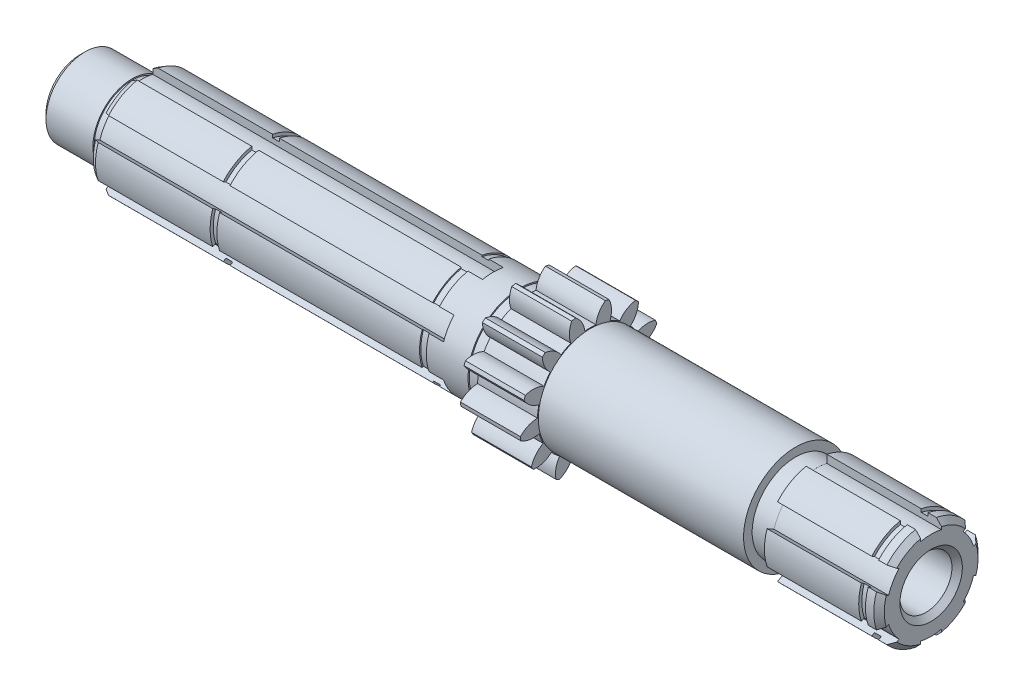
SolidWorks part; units mm, degrees
ref_plane "前视基准面" through (0, 0, 0) normal (0, 0, 1) x (1, 0, 0)
ref_plane "上视基准面" through (0, 0, 0) normal (0, 1, 0) x (1, 0, 0)
ref_plane "右视基准面" through (0, 0, 0) normal (1, 0, 0) x (0, 0, -1)
sketch "草图1" plane through (0, 0, 0) normal (0, 0, 1) x (1, 0, 0)
  line L0 (-46.8808, 0) -> (68.5307, 0) construction
  line L1 (-80.9834, 0) -> (-80.9834, 7.5)
  line L2 (-80.9834, 7.5) -> (-70.9834, 7.5)
  line L3 (-70.9834, 7.5) -> (-70.9834, 7.25)
  line L4 (-70.9834, 7.25) -> (-68.9834, 7.25)
  line L5 (-68.9834, 7.25) -> (-68.9834, 10)
  line L6 (-68.9834, 10) -> (-45.9834, 10)
  line L7 (-45.9834, 10) -> (-45.9834, 9.4)
  line L8 (-45.9834, 9.4) -> (-44.6834, 9.4)
  line L9 (-44.6834, 9.4) -> (-44.6834, 10)
  line L10 (-44.6834, 10) -> (-5.7834, 10)
  line L11 (-5.7834, 10) -> (-5.7834, 9.75)
  line L12 (-5.7834, 9.75) -> (-4.4834, 9.75)
  line L13 (-4.4834, 9.75) -> (-4.4834, 10)
  line L14 (-4.4834, 10) -> (3.5166, 10)
  line L15 (3.5166, 10) -> (3.5166, 9.75)
  line L16 (3.5166, 9.75) -> (5.5166, 9.75)
  line L17 (-80.9834, 0) -> (5.5166, 0)
  line L18 (5.5166, 9.75) -> (5.5166, 0)
  point P20 (0, 0)
  dimension "D1" = 7.5
  dimension "D2" = 10
  dimension "D3" = 10
  dimension "D4" = 0.6
  dimension "D5" = 9.75
  dimension "D6" = 75.2
  dimension "D7" = 35
  dimension "D8" = 36.3
  dimension "D9" = 10
  dimension "D10" = 84.5
  dimension "D11" = 86.5
revolve "旋转1" add sketch "草图1" angle 360 about L0
sketch "草图4" plane through (5.5166, 0, 0) normal (1, 0, 0) x (0, 0, -1)
  arc A0 (2.8664, 13.1922) -> (1.0583, 10.0947) centre (5.5738, 9.5354) ccw
  arc A1 (3.7542, 9.4302) -> (3.5927, 13.0132) centre (-0.504, 11.0334) ccw
  arc A2 (3.5927, 13.0132) -> (2.8664, 13.1922) centre (0, 0) ccw
  arc A3 (8.6687, 10.349) -> (5.6283, 8.4466) centre (9.3666, 5.8529) ccw
  arc A4 (7.7066, 6.6054) -> (9.2287, 9.853) centre (4.6812, 10.0038) ccw
  arc A5 (-1.0583, 10.0947) -> (-2.8664, 13.1922) centre (-5.5738, 9.5354) ccw
  arc A6 (-2.8664, 13.1922) -> (-3.5927, 13.0132) centre (0, 0) ccw
  arc A7 (-3.5927, 13.0132) -> (-3.7542, 9.4302) centre (0.504, 11.0334) ccw
  arc A8 (9.2287, 9.853) -> (8.6687, 10.349) centre (0, 0) ccw
  arc A9 (12.4852, 5.1351) -> (8.9089, 4.8635) centre (11.0137, 0.8296) ccw
  arc A10 (9.8935, 2.2673) -> (12.7505, 4.4356) centre (8.794, 6.6825) ccw
  arc A11 (12.7505, 4.4356) -> (12.4852, 5.1351) centre (0, 0) ccw
  arc A12 (13.4415, -1.2553) -> (10.1486, 0.1662) centre (10.1377, -4.3838) ccw
  arc A13 (9.814, -2.5901) -> (13.3513, -1.9979) centre (10.8922, 1.8303) ccw
  arc A14 (13.3513, -1.9979) -> (13.4415, -1.2553) centre (0, 0) ccw
  arc A15 (11.3185, -7.3581) -> (9.0634, -4.5691) centre (6.9392, -8.5929) ccw
  arc A16 (7.4861, -6.8542) -> (10.8935, -7.9738) centre (10.4951, -3.4412) ccw
  arc A17 (10.8935, -7.9738) -> (11.3185, -7.3581) centre (0, 0) ccw
  arc A18 (6.6025, -11.7752) -> (5.9019, -8.2577) centre (2.1511, -10.8334) ccw
  arc A19 (3.4433, -9.5481) -> (5.9402, -12.1229) centre (7.6938, -7.9244) ccw
  arc A20 (5.9402, -12.1229) -> (6.6025, -11.7752) centre (0, 0) ccw
  arc A21 (0.374, -13.4948) -> (1.3883, -10.0546) centre (-3.1298, -10.5922) ccw
  arc A22 (-1.3883, -10.0546) -> (-0.374, -13.4948) centre (3.1298, -10.5922) ccw
  arc A23 (-0.374, -13.4948) -> (0.374, -13.4948) centre (0, 0) ccw
  arc A24 (-5.9402, -12.1229) -> (-3.4433, -9.5481) centre (-7.6938, -7.9244) ccw
  arc A25 (-5.9019, -8.2577) -> (-6.6025, -11.7752) centre (-2.1511, -10.8334) ccw
  arc A26 (-6.6025, -11.7752) -> (-5.9402, -12.1229) centre (0, 0) ccw
  arc A27 (-10.8935, -7.9738) -> (-7.4861, -6.8542) centre (-10.4951, -3.4412) ccw
  arc A28 (-9.0634, -4.5691) -> (-11.3185, -7.3581) centre (-6.9392, -8.5929) ccw
  arc A29 (-11.3185, -7.3581) -> (-10.8935, -7.9738) centre (0, 0) ccw
  arc A30 (-13.3513, -1.9979) -> (-9.814, -2.5901) centre (-10.8922, 1.8303) ccw
  arc A31 (-10.1486, 0.1662) -> (-13.4415, -1.2553) centre (-10.1377, -4.3838) ccw
  arc A32 (-13.4415, -1.2553) -> (-13.3513, -1.9979) centre (0, 0) ccw
  arc A33 (-12.7505, 4.4356) -> (-9.8935, 2.2673) centre (-8.794, 6.6825) ccw
  arc A34 (-8.9089, 4.8635) -> (-12.4852, 5.1351) centre (-11.0137, 0.8296) ccw
  arc A35 (-12.4852, 5.1351) -> (-12.7505, 4.4356) centre (0, 0) ccw
  arc A36 (-9.2287, 9.853) -> (-7.7066, 6.6054) centre (-4.6812, 10.0038) ccw
  arc A37 (-5.6283, 8.4466) -> (-8.6687, 10.349) centre (-9.3666, 5.8529) ccw
  arc A38 (-8.6687, 10.349) -> (-9.2287, 9.853) centre (0, 0) ccw
  arc A39 (-9.814, -2.5901) -> (-9.0634, -4.5691) centre (0, 0) ccw
  arc A40 (-7.4861, -6.8542) -> (-5.9019, -8.2577) centre (0, 0) ccw
  arc A41 (-3.4433, -9.5481) -> (-1.3883, -10.0546) centre (0, 0) ccw
  arc A42 (1.3883, -10.0546) -> (3.4433, -9.5481) centre (0, 0) ccw
  arc A43 (5.9019, -8.2577) -> (7.4861, -6.8542) centre (0, 0) ccw
  arc A44 (9.0634, -4.5691) -> (9.814, -2.5901) centre (0, 0) ccw
  arc A45 (10.1486, 0.1662) -> (9.8935, 2.2673) centre (0, 0) ccw
  arc A46 (8.9089, 4.8635) -> (7.7066, 6.6054) centre (0, 0) ccw
  arc A47 (5.6283, 8.4466) -> (3.7542, 9.4302) centre (0, 0) ccw
  arc A48 (1.0583, 10.0947) -> (-1.0583, 10.0947) centre (0, 0) ccw
  arc A49 (-3.7542, 9.4302) -> (-5.6283, 8.4466) centre (0, 0) ccw
  arc A50 (-7.7066, 6.6054) -> (-8.9089, 4.8635) centre (0, 0) ccw
  arc A51 (-9.8935, 2.2673) -> (-10.1486, 0.1662) centre (0, 0) ccw
  point P82 (0, 0)
  dimension "D2" = 13.5
  dimension "D3" = 20.3
  dimension "D1" = 13
extrude "凸台-拉伸1" add sketch "草图4" along normal blind 11.5
sketch "草图5" plane through (0, 0, 0) normal (0, 0, 1) x (1, 0, 0)
  line L0 (30.7294, 0) -> (-10.5203, 0) construction
  line L1 (12.0035, 0) -> (17.0166, 9.75)
  line L2 (17.0166, 6.6054) -> (17.0166, 9.853) construction
  line L3 (17.0166, 9.75) -> (14.0166, 9.75)
  line L4 (14.0166, 9.75) -> (14.0166, 10)
  line L5 (14.0166, 10) -> (56.4166, 10)
  line L6 (56.4166, 10) -> (56.4166, 8.35)
  line L7 (56.4166, 8.35) -> (60.4166, 8.35)
  line L8 (60.4166, 8.35) -> (60.4166, 10)
  line L9 (60.4166, 10) -> (78.5166, 10)
  line L10 (78.5166, 10) -> (78.5166, 9.4)
  line L11 (78.5166, 9.4) -> (79.8166, 9.4)
  line L12 (79.8166, 9.4) -> (79.8166, 10)
  line L13 (79.8166, 10) -> (82.4166, 10)
  line L14 (82.4166, 10) -> (82.4166, 0)
  line L15 (82.4166, 0) -> (12.0035, 0)
revolve "旋转2" add sketch "草图5" angle 360 about L15
sketch "草图6" plane through (-68.9834, 0, 0) normal (-1, 0, 0) x (0, 0, 1)
  line L0 (0, 10.7759) -> (0, -4.9329) construction
  line L1 (7.4853, 6.631) -> (6.1545, 5.8627)
  line L2 (-2, 9.798) -> (-2, 8.2614)
  line L3 (2, 9.798) -> (2, 8.2614)
  line L4 (9.4853, 3.1669) -> (8.1545, 2.3986)
  line L5 (9.4853, -3.1669) -> (8.1545, -2.3986)
  line L6 (7.4853, -6.631) -> (6.1545, -5.8627)
  line L7 (2, -9.798) -> (2, -8.2614)
  line L8 (-2, -9.798) -> (-2, -8.2614)
  line L9 (-7.4853, -6.631) -> (-6.1545, -5.8627)
  line L10 (-9.4853, -3.1669) -> (-8.1545, -2.3986)
  line L11 (-9.4853, 3.1669) -> (-8.1545, 2.3986)
  line L12 (-7.4853, 6.631) -> (-6.1545, 5.8627)
  arc A0 (-6.1545, 5.8627) -> (-8.1545, 2.3986) centre (0, 0) ccw
  circle A1 centre (0, 0) radius 10 construction
  arc A2 (2, 9.798) -> (-2, 9.798) centre (0, 0) ccw
  arc A3 (9.4853, 3.1669) -> (7.4853, 6.631) centre (0, 0) ccw
  arc A4 (7.4853, -6.631) -> (9.4853, -3.1669) centre (0, 0) ccw
  arc A5 (-2, -9.798) -> (2, -9.798) centre (0, 0) ccw
  arc A6 (-9.4853, -3.1669) -> (-7.4853, -6.631) centre (0, 0) ccw
  arc A7 (-7.4853, 6.631) -> (-9.4853, 3.1669) centre (0, 0) ccw
  arc A8 (2, 8.2614) -> (-2, 8.2614) centre (0, 0) ccw
  arc A9 (8.1545, 2.3986) -> (6.1545, 5.8627) centre (0, 0) ccw
  arc A10 (6.1545, -5.8627) -> (8.1545, -2.3986) centre (0, 0) ccw
  arc A11 (-2, -8.2614) -> (2, -8.2614) centre (0, 0) ccw
  arc A12 (-8.1545, -2.3986) -> (-6.1545, -5.8627) centre (0, 0) ccw
  point P10 (0, 9.798)
  point P35 (0, 0)
  dimension "D1" = 17
  dimension "D3" = 6
  dimension "D2" = 2
extrude "切除-拉伸3" cut sketch "草图6" against normal blind 67.3
sketch "草图7" plane through (82.4166, 0, 0) normal (1, 0, 0) x (0, 0, -1)
  line L0 (7.4853, 6.631) -> (6.1545, 5.8627)
  line L1 (-2, 9.798) -> (-2, 8.2614)
  line L2 (2, 9.798) -> (2, 8.2614)
  line L3 (9.4853, 3.1669) -> (8.1545, 2.3986)
  line L4 (9.4853, -3.1669) -> (8.1545, -2.3986)
  line L5 (7.4853, -6.631) -> (6.1545, -5.8627)
  line L6 (2, -9.798) -> (2, -8.2614)
  line L7 (-2, -9.798) -> (-2, -8.2614)
  line L8 (-7.4853, -6.631) -> (-6.1545, -5.8627)
  line L9 (-9.4853, -3.1669) -> (-8.1545, -2.3986)
  line L10 (-9.4853, 3.1669) -> (-8.1545, 2.3986)
  line L11 (-7.4853, 6.631) -> (-6.1545, 5.8627)
  arc A0 (-6.1545, 5.8627) -> (-8.1545, 2.3986) centre (0, 0) ccw
  arc A1 (2, 9.798) -> (-2, 9.798) centre (0, 0) ccw
  arc A2 (9.4853, 3.1669) -> (7.4853, 6.631) centre (0, 0) ccw
  arc A3 (7.4853, -6.631) -> (9.4853, -3.1669) centre (0, 0) ccw
  arc A4 (-2, -9.798) -> (2, -9.798) centre (0, 0) ccw
  arc A5 (-9.4853, -3.1669) -> (-7.4853, -6.631) centre (0, 0) ccw
  arc A6 (-7.4853, 6.631) -> (-9.4853, 3.1669) centre (0, 0) ccw
  arc A7 (2, 8.2614) -> (-2, 8.2614) centre (0, 0) ccw
  arc A8 (8.1545, 2.3986) -> (6.1545, 5.8627) centre (0, 0) ccw
  arc A9 (6.1545, -5.8627) -> (8.1545, -2.3986) centre (0, 0) ccw
  arc A10 (-2, -8.2614) -> (2, -8.2614) centre (0, 0) ccw
  arc A11 (-8.1545, -2.3986) -> (-6.1545, -5.8627) centre (0, 0) ccw
  point P3 (0, 9.798)
  point P26 (-5.8073, -0.3567)
  point P27 (0, 0)
  dimension "D1" = 17
  dimension "D2" = 2
extrude "切除-拉伸4" cut sketch "草图7" along direction (-1, 0, 0) on the side against the normal up to next (22 mm away)
sketch "草图8" plane through (-80.9834, 0, 0) normal (-1, 0, 0) x (0, 0, 1)
  circle A0 centre (0, 0) radius 4
  dimension "D1" = 8
extrude "切除-拉伸5" cut sketch "草图8" against normal through all
sketch "草图9" plane through (82.4166, 0, 0) normal (1, 0, 0) x (0, 0, -1)
  circle A0 centre (0, 0) radius 5
extrude "切除-拉伸7" cut sketch "草图9" along direction (-1, 0, 0) on the side against the normal up to surface (78.9 mm away)
chamfer "倒角1" distance 1 angle 45 7 edges at (82.4166, 0, -5)
chamfer "倒角2" distance 1 angle 45 2 edges at (-80.9834, 0, 4) (-80.9834, 0, 7.5)
chamfer "倒角3" distance 1 angle 30 6 edges at (-68.9834, 0, 10) (-68.9834, -8.6603, 5) (-68.9834, -8.6603, -5) (-68.9834, 0, -10) (-68.9834, 8.6603, 5) (-68.9834, 8.6603, -5)
sketch "草图10" plane through (0, 0, 0) normal (0, 1, 0) x (1, 0, 0)
  line L0 (-96.0854, 0) -> (89.4167, 0) construction
  line L1 (82.4166, -2) -> (82.4166, 2) construction
  line L2 (-80.9834, 6.5) -> (-80.9834, -6.5) construction
  circle A0 centre (35.4166, 0) radius 1
  circle A1 centre (-51.9834, 0) radius 1
  dimension "D1" = 47
  dimension "D2" = 29
extrude "切除-拉伸8" cut sketch "草图10" against normal blind 10
